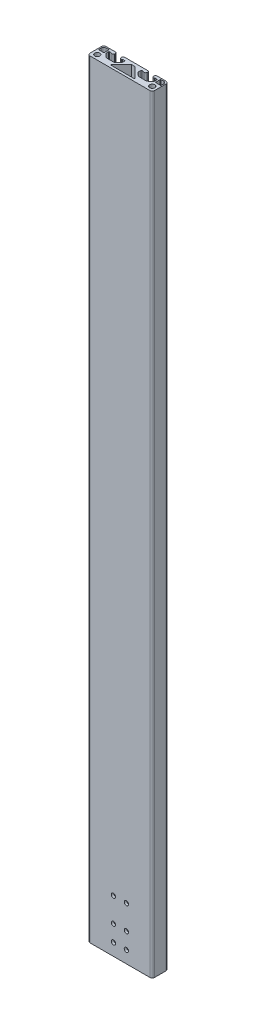
SolidWorks part; units mm, degrees
ref_plane "Front Plane" through (0, 0, 0) normal (0, 0, 1) x (1, 0, 0)
ref_plane "Top Plane" through (0, 0, 0) normal (0, 1, 0) x (1, 0, 0)
ref_plane "Right Plane" through (0, 0, 0) normal (1, 0, 0) x (0, 0, -1)
ref_plane "Plane1" through (0, 0, 0) normal (0, -1, 0) x (1, 0, 0)
sketch "Sketch1" plane through (0, 0, 0) normal (0, -1, 0) x (1, 0, 0)
  line L0 (7.45, -18.5) -> (4.3, -18.5)
  line L1 (1.5, -15.7) -> (1.5, -12.75)
  line L2 (2.25, -12) -> (7.45, -12)
  line L3 (8.2, -12.75) -> (8.2, -17.75)
  line L4 (54.5464, -3.8536) -> (41.9, -16.5)
  line L5 (41.9, -16.5) -> (38.1, -16.5)
  line L6 (38.1, -16.5) -> (25.4536, -3.8536)
  line L7 (25.8071, -3) -> (54.1929, -3)
  line L8 (71.8, -17.75) -> (71.8, -12.75)
  line L9 (72.55, -12) -> (77.75, -12)
  line L10 (78.5, -12.75) -> (78.5, -15.7)
  line L11 (75.7, -18.5) -> (72.55, -18.5)
  line L12 (77, 0) -> (3, 0)
  line L13 (0, -3) -> (0, -17)
  line L14 (3, -20) -> (14.5, -20)
  line L15 (16, -18.5) -> (16, -17.5)
  line L16 (14.5, -16) -> (13.2, -16)
  line L17 (13.2, -16) -> (13.2, -16.5)
  line L18 (13.2, -16.5) -> (10.75, -16.5)
  line L19 (10, -15.75) -> (10, -12.8107)
  line L20 (10.2197, -12.2803) -> (13.1088, -9.3912)
  line L21 (16.4675, -8) -> (23.5325, -8)
  line L22 (26.8912, -9.3912) -> (29.7803, -12.2803)
  line L23 (30, -12.8107) -> (30, -15.75)
  line L24 (29.25, -16.5) -> (26.8, -16.5)
  line L25 (26.8, -16.5) -> (26.8, -16)
  line L26 (26.8, -16) -> (25.5, -16)
  line L27 (24, -17.5) -> (24, -18.5)
  line L28 (25.5, -20) -> (54.5, -20)
  line L29 (56, -18.5) -> (56, -17.5)
  line L30 (54.5, -16) -> (53.2, -16)
  line L31 (53.2, -16) -> (53.2, -16.5)
  line L32 (53.2, -16.5) -> (50.75, -16.5)
  line L33 (50, -15.75) -> (50, -12.8107)
  line L34 (50.2197, -12.2803) -> (53.1088, -9.3912)
  line L35 (56.4675, -8) -> (63.5325, -8)
  line L36 (66.8912, -9.3912) -> (69.7803, -12.2803)
  line L37 (70, -12.8107) -> (70, -15.75)
  line L38 (69.25, -16.5) -> (66.8, -16.5)
  line L39 (66.8, -16.5) -> (66.8, -16)
  line L40 (66.8, -16) -> (65.5, -16)
  line L41 (64, -17.5) -> (64, -18.5)
  line L42 (65.5, -20) -> (77, -20)
  line L43 (80, -17) -> (80, -3)
  circle A0 centre (6, -6) radius 3.175
  arc A1 (8.2, -17.75) -> (7.45, -18.5) centre (7.45, -17.75) cw
  arc A2 (4.3, -18.5) -> (1.5, -15.7) centre (4.3, -15.7) cw
  arc A3 (1.5, -12.75) -> (2.25, -12) centre (2.25, -12.75) cw
  arc A4 (7.45, -12) -> (8.2, -12.75) centre (7.45, -12.75) cw
  arc A5 (25.4536, -3.8536) -> (25.8071, -3) centre (25.8071, -3.5) cw
  arc A6 (54.1929, -3) -> (54.5464, -3.8536) centre (54.1929, -3.5) cw
  circle A7 centre (74, -6) radius 3.175
  arc A8 (72.55, -18.5) -> (71.8, -17.75) centre (72.55, -17.75) cw
  arc A9 (71.8, -12.75) -> (72.55, -12) centre (72.55, -12.75) cw
  arc A10 (77.75, -12) -> (78.5, -12.75) centre (77.75, -12.75) cw
  arc A11 (78.5, -15.7) -> (75.7, -18.5) centre (75.7, -15.7) cw
  arc A12 (80, -3) -> (77, 0) centre (77, -3) ccw
  arc A13 (3, 0) -> (0, -3) centre (3, -3) ccw
  arc A14 (0, -17) -> (3, -20) centre (3, -17) ccw
  arc A15 (14.5, -20) -> (16, -18.5) centre (14.5, -18.5) ccw
  arc A16 (16, -17.5) -> (14.5, -16) centre (14.5, -17.5) ccw
  arc A17 (10.75, -16.5) -> (10, -15.75) centre (10.75, -15.75) cw
  arc A18 (10, -12.8107) -> (10.2197, -12.2803) centre (10.75, -12.8107) cw
  arc A19 (13.1088, -9.3912) -> (16.4675, -8) centre (16.4675, -12.75) cw
  arc A20 (23.5325, -8) -> (26.8912, -9.3912) centre (23.5325, -12.75) cw
  arc A21 (29.7803, -12.2803) -> (30, -12.8107) centre (29.25, -12.8107) cw
  arc A22 (30, -15.75) -> (29.25, -16.5) centre (29.25, -15.75) cw
  arc A23 (25.5, -16) -> (24, -17.5) centre (25.5, -17.5) ccw
  arc A24 (24, -18.5) -> (25.5, -20) centre (25.5, -18.5) ccw
  arc A25 (54.5, -20) -> (56, -18.5) centre (54.5, -18.5) ccw
  arc A26 (56, -17.5) -> (54.5, -16) centre (54.5, -17.5) ccw
  arc A27 (50.75, -16.5) -> (50, -15.75) centre (50.75, -15.75) cw
  arc A28 (50, -12.8107) -> (50.2197, -12.2803) centre (50.75, -12.8107) cw
  arc A29 (53.1088, -9.3912) -> (56.4675, -8) centre (56.4675, -12.75) cw
  arc A30 (63.5325, -8) -> (66.8912, -9.3912) centre (63.5325, -12.75) cw
  arc A31 (69.7803, -12.2803) -> (70, -12.8107) centre (69.25, -12.8107) cw
  arc A32 (70, -15.75) -> (69.25, -16.5) centre (69.25, -15.75) cw
  arc A33 (65.5, -16) -> (64, -17.5) centre (65.5, -17.5) ccw
  arc A34 (64, -18.5) -> (65.5, -20) centre (65.5, -18.5) ccw
  arc A35 (77, -20) -> (80, -17) centre (77, -17) ccw
extrude "Boss-Extrude1" add sketch "Sketch1" against normal blind 950
ref_plane "Mid-Plane" through (40, 0, 0) normal (1, 0, 0) x (0, 0, -1)
ref_plane "belt_mid" through (60, 0, 0) normal (1, 0, 0) x (0, 0, -1)
ref_plane "belt_mid_2" through (20, 0, 0) normal (-1, 0, 0) x (0, 0, 1)
hole_wizard "M5 Clearance Hole1" positions "Sketch2" profile "Sketch3" hole size "M5" standard "ANSI Metric"
sketch "Sketch2" plane through (0, 0, 0) normal (0, 0, 1) x (1, 0, 0)
  point P0 (48, 15)
  point P3 (48, 35)
  point P6 (48, 65)
  point P9 (32, 65)
  point P12 (32, 35)
  point P15 (32, 15)
sketch "Sketch3" plane through (48, 15, 0) normal (1, 0, 0) x (0, -1, 0)
  line L0 (0, 0) -> (0, 6.5923)
  line L1 (0, 6.5923) -> (2.65, 5)
  line L2 (2.65, 5) -> (2.65, 0)
  line L5 (2.65, 0) -> (0, 0)
  line L10 (0, 6.5923) -> (-2.65, 5) construction
  line L11 (0, -6.35) -> (0, 107.95) construction
  dimension "Hole Dia." = 5.3
  dimension "Hole Depth" = 5
  dimension "Drill Angle" = 118
